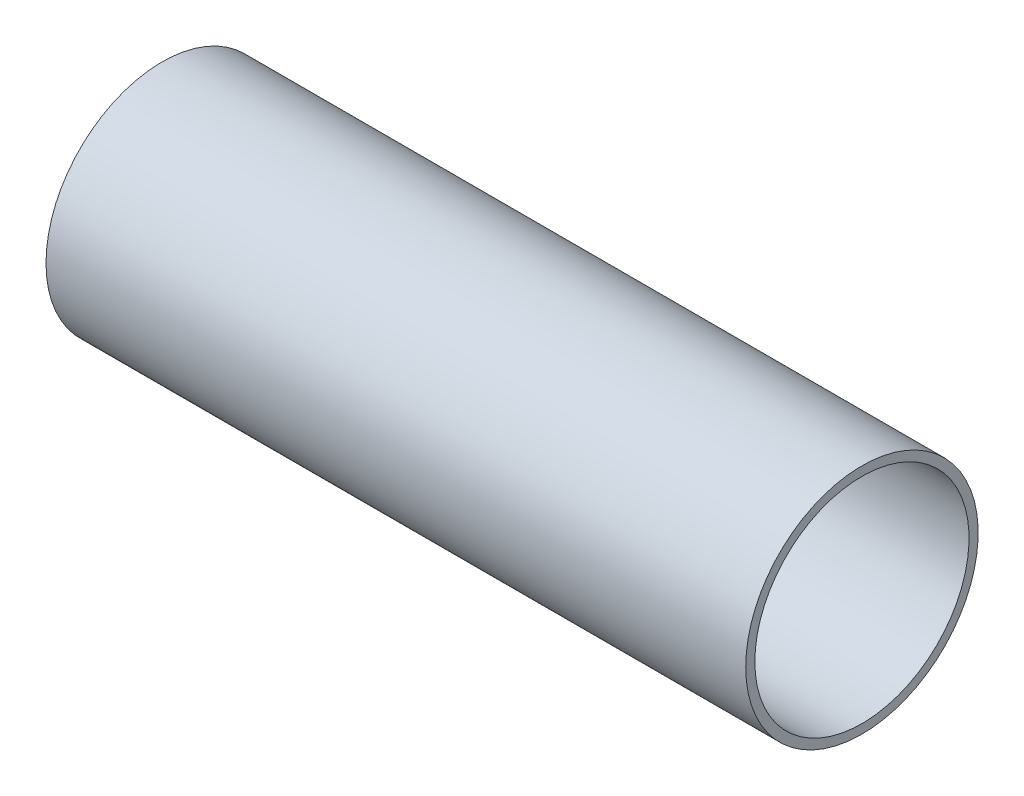
SolidWorks part; units mm, degrees
material "6061-T6 (SS)"
ref_plane "Front Plane" through (0, 0, 0) normal (0, 0, 1) x (1, 0, 0)
ref_plane "Top Plane" through (0, 0, 0) normal (0, 1, 0) x (1, 0, 0)
ref_plane "Right Plane" through (0, 0, 0) normal (1, 0, 0) x (0, 0, -1)
sketch "Sketch1" plane through (0, 0, 0) normal (0, 1, 0) x (1, 0, 0)
  line L0 (-72.894, 0) -> (78.2697, 0) construction
  line L1 (-47.7901, 15.875) -> (-47.7901, 14.6304)
  line L2 (-47.7901, 15.875) -> (47.7901, 15.875)
  line L3 (-47.7901, 14.6304) -> (47.7901, 14.6304)
  line L4 (47.7901, 15.875) -> (47.7901, 14.6304)
  line L5 (0, 0) -> (0, 14.6304) construction
  dimension "D1" = 31.75
  dimension "D2" = 1.2446
  dimension "D3" = 95.5802
revolve "Revolve1" add sketch "Sketch1" angle 360 about L0
